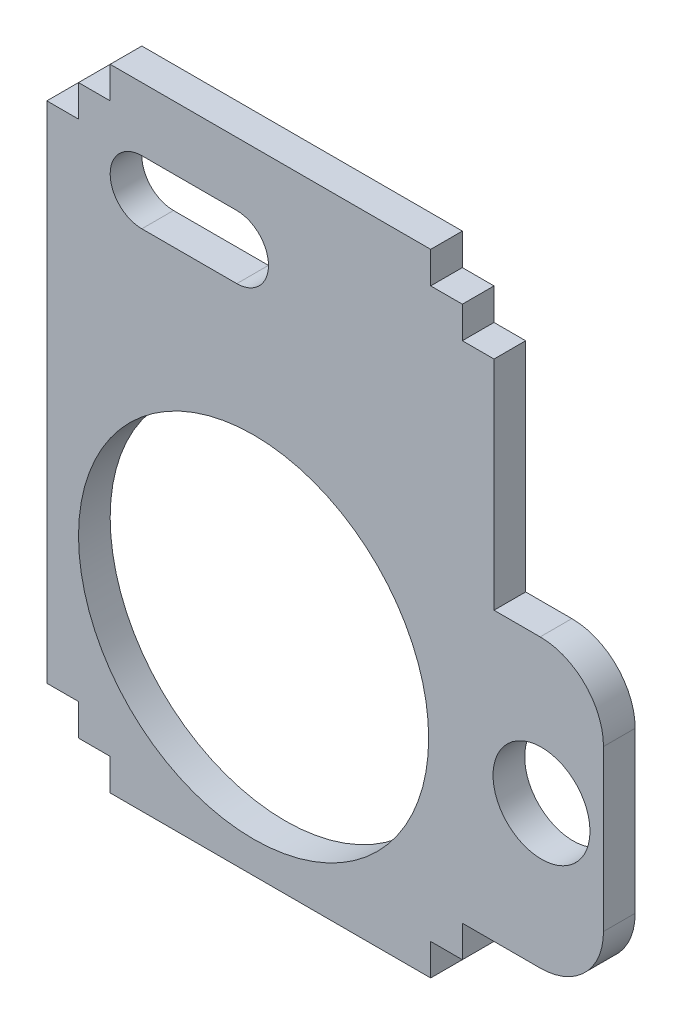
SolidWorks part; units mm, degrees
material "Acrylic (Medium-high impact)"
ref_plane "Front Plane" through (0, 0, 0) normal (0, 0, 1) x (1, 0, 0)
ref_plane "Top Plane" through (0, 0, 0) normal (0, 1, 0) x (1, 0, 0)
ref_plane "Right Plane" through (0, 0, 0) normal (1, 0, 0) x (0, 0, -1)
sketch "Sketch1" plane through (0, 0, 0) normal (0, 0, 1) x (1, 0, 0)
  line L1 (75.0624, -16.1337) -> (75.0624, 15.9973)
  line L2 (78.2374, 111.3108) -> (78.2374, -41.2162) construction
  line L29 (-30.2333, -28.8337) -> (-30.2333, -35.1837)
  line L30 (-36.5833, -28.8337) -> (-30.2333, -28.8337)
  line L31 (-36.5833, 72.3345) -> (-36.5833, -28.8337)
  line L32 (-30.2333, 72.3345) -> (-36.5833, 72.3345)
  line L33 (-30.2333, 78.6845) -> (-30.2333, 72.3345)
  line L34 (-23.8833, 78.6845) -> (-30.2333, 78.6845)
  line L35 (-23.8833, 85.0345) -> (-23.8833, 78.6845)
  line L36 (40.4041, 85.0345) -> (-23.8833, 85.0345)
  line L37 (40.4041, 78.6845) -> (40.4041, 85.0345)
  line L38 (46.7541, 78.6845) -> (40.4041, 78.6845)
  line L39 (46.7541, 72.3345) -> (46.7541, 78.6845)
  line L40 (53.1041, 72.3345) -> (46.7541, 72.3345)
  line L41 (53.1041, 28.6973) -> (53.1041, 72.3345)
  line L42 (100.183, 28.6973) -> (53.1041, 28.6973)
  line L43 (112.883, -16.1337) -> (112.883, 15.9973)
  line L44 (46.7541, -28.8337) -> (100.183, -28.8337)
  line L45 (46.7541, -35.1837) -> (46.7541, -28.8337)
  line L46 (40.4041, -35.1837) -> (46.7541, -35.1837)
  line L47 (40.4041, -41.5337) -> (40.4041, -35.1837)
  line L48 (-23.8833, -41.5337) -> (40.4041, -41.5337)
  line L49 (-23.8833, -35.1837) -> (-23.8833, -41.5337)
  line L50 (-30.2333, -35.1837) -> (-23.8833, -35.1837)
  line L51 (-30.2333, -28.8337) -> (-30.2333, -35.1837)
  line L52 (-36.5833, -28.8337) -> (-30.2333, -28.8337)
  line L53 (-36.5833, 72.3345) -> (-36.5833, -28.8337)
  line L54 (-30.2333, 72.3345) -> (-36.5833, 72.3345)
  line L55 (-30.2333, 78.6845) -> (-30.2333, 72.3345)
  line L56 (-23.8833, 78.6845) -> (-30.2333, 78.6845)
  line L57 (-23.8833, 85.0345) -> (-23.8833, 78.6845)
  line L58 (40.4041, 85.0345) -> (-23.8833, 85.0345)
  line L59 (40.4041, 78.6845) -> (40.4041, 85.0345)
  line L60 (46.7541, 78.6845) -> (40.4041, 78.6845)
  line L61 (46.7541, 72.3345) -> (46.7541, 78.6845)
  line L62 (53.1041, 72.3345) -> (46.7541, 72.3345)
  line L63 (53.1041, 28.6973) -> (53.1041, 72.3345)
  line L64 (62.3624, 28.6973) -> (53.1041, 28.6973)
  line L66 (46.7541, -28.8337) -> (62.3624, -28.8337)
  line L67 (46.7541, -35.1837) -> (46.7541, -28.8337)
  line L68 (40.4041, -35.1837) -> (46.7541, -35.1837)
  line L69 (40.4041, -41.5337) -> (40.4041, -35.1837)
  line L70 (-23.8833, -41.5337) -> (40.4041, -41.5337)
  line L71 (-23.8833, -35.1837) -> (-23.8833, -41.5337)
  line L72 (-30.2333, -35.1837) -> (-23.8833, -35.1837)
  circle A1 centre (4.8822, -0.0682) radius 35.1155 construction
  circle A2 centre (4.8822, -0.0682) radius 35.1155
  circle A3 centre (62.6291, -0.0682) radius 9.7234 construction
  circle A4 centre (62.6291, -0.0682) radius 9.7234
  arc A5 (112.883, 15.9973) -> (100.183, 28.6973) centre (100.183, 15.9973) ccw
  arc A6 (75.0624, 15.9973) -> (62.3624, 28.6973) centre (62.3624, 15.9973) ccw
  arc A7 (100.183, -28.8337) -> (112.883, -16.1337) centre (100.183, -16.1337) ccw
  arc A8 (75.0624, -16.1337) -> (62.3624, -28.8337) centre (62.3624, -16.1337) cw
  dimension "D3" = 12.7
  dimension "D1" = 0
  dimension "D2" = 3.175
extrude "Boss-Extrude1" add sketch "Sketch1" against normal blind 6.35
sketch "Sketch2" plane through (0, 0, 0) normal (0, 0, 1) x (1, 0, 0)
  line L0 (-17.5333, 59.6345) -> (1.5167, 59.6345)
  line L1 (1.5167, 72.3345) -> (-17.5333, 72.3345)
  line L2 (-36.5833, 72.3345) -> (-36.5833, -28.8337) construction
  line L3 (-23.8833, 78.6845) -> (40.4041, 78.6845) construction
  arc A0 (1.5167, 59.6345) -> (1.5167, 72.3345) centre (1.5167, 65.9845) ccw
  arc A1 (-17.5333, 72.3345) -> (-17.5333, 59.6345) centre (-17.5333, 65.9845) ccw
  dimension "D1" = 6.35
  dimension "D3" = 19.05
  dimension "D2" = 19.05
  dimension "D4" = 6.35
extrude "Cut-Extrude1" cut sketch "Sketch2" against normal through all
